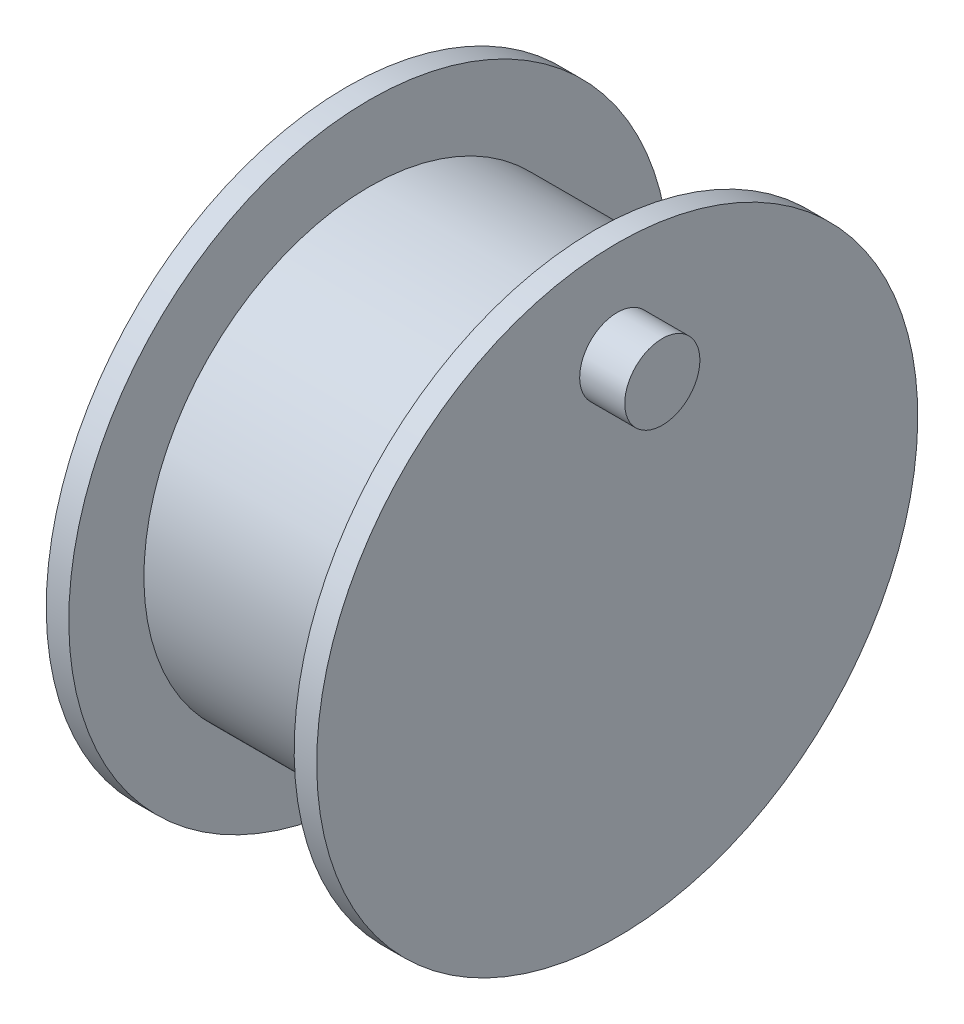
SolidWorks part; units mm, degrees
material "Alumina"
ref_plane "Front Plane" through (0, 0, 0) normal (0, 0, 1) x (1, 0, 0)
ref_plane "Top Plane" through (0, 0, 0) normal (0, 1, 0) x (1, 0, 0)
ref_plane "Right Plane" through (0, 0, 0) normal (1, 0, 0) x (0, 0, -1)
sketch "Sketch4" plane through (0, 0, 0) normal (0, 0, 1) x (1, 0, 0)
  line L0 (-7.5, 15) -> (7.5, 15)
  line L1 (7.5, 15) -> (7.5, 20)
  line L2 (7.5, 20) -> (9, 20)
  line L3 (9, 20) -> (9, 0)
  line L4 (9, 0) -> (-9, 0)
  line L5 (-9, 0) -> (-9, 20)
  line L6 (-9, 20) -> (-7.5, 20)
  line L7 (-7.5, 20) -> (-7.5, 15)
  dimension "D1" = 1.5
  dimension "D2" = 15
  dimension "D3" = 18
  dimension "D4" = 1.5
  dimension "D5" = 15
  dimension "D6" = 5
  dimension "D7" = 9
revolve "Revolve1" add sketch "Sketch4" angle 360 about L4
sketch "Sketch6" plane through (9, 0, 0) normal (1, 0, 0) x (0, 0, -1)
  line L0 (0, 0) -> (0, 13.5) construction
  circle A0 centre (0, 13.5) radius 2.5
  dimension "D1" = 5
  dimension "D2" = 13.5
extrude "Boss-Extrude2" add sketch "Sketch6" along normal blind 3
sketch "Sketch7" plane through (-9, 0, 0) normal (-1, 0, 0) x (0, 0, 1)
  circle A2 centre (0, 0) radius 3
  dimension "D1" = 6
extrude "Cut-Extrude2" cut sketch "Sketch7" against normal blind 16
